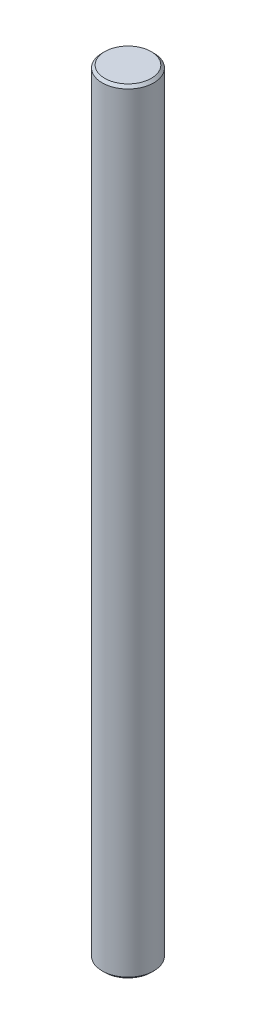
SolidWorks part; units mm, degrees
material "AISI 1045 Steel, cold drawn"
ref_plane "Front Plane" through (0, 0, 0) normal (0, 0, 1) x (1, 0, 0)
ref_plane "Top Plane" through (0, 0, 0) normal (0, 1, 0) x (1, 0, 0)
ref_plane "Right Plane" through (0, 0, 0) normal (1, 0, 0) x (0, 0, -1)
sketch "Sketch1" plane through (0, 0, 0) normal (0, 1, 0) x (1, 0, 0)
  circle A0 centre (0, 0) radius 2.5
  dimension "D1" = 5
extrude "Boss-Extrude1" add sketch "Sketch1" along normal mid plane 75
chamfer "Chamfer1" distance 0.25 angle 45 2 edges at (0, -37.5, 2.5) (0, 37.5, 2.5)
